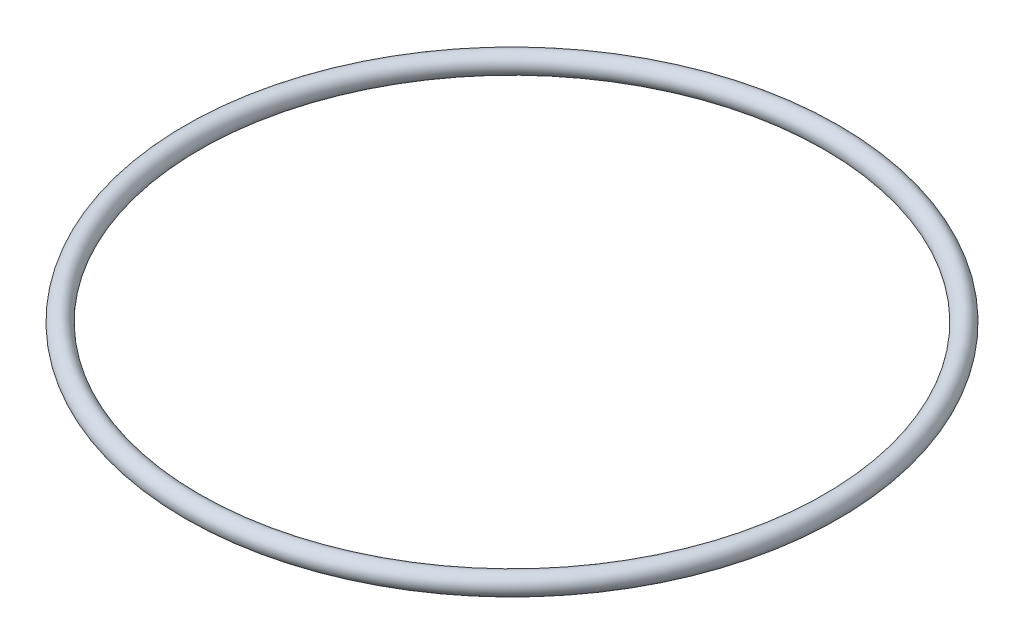
SolidWorks part; units mm, degrees
ref_plane "Front Plane" through (0, 0, 0) normal (0, 0, 1) x (1, 0, 0)
ref_plane "Top Plane" through (0, 0, 0) normal (0, 1, 0) x (1, 0, 0)
ref_plane "Right Plane" through (0, 0, 0) normal (1, 0, 0) x (0, 0, -1)
sketch "Reconstructed nominal axial profile" plane through (0, 0, 0) normal (0, 0, 1) x (1, 0, 0)
  line L0 (0, -500) -> (0, 50) construction
  circle A0 centre (32, 0) radius 1
revolve "Native revolved geometry" add sketch "Reconstructed nominal axial profile" angle 360 about L0
